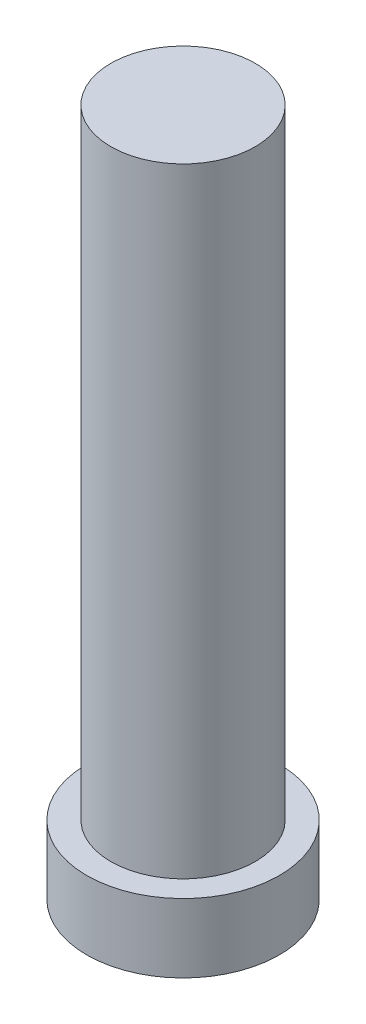
SolidWorks part; units mm, degrees
ref_plane "Front Plane" through (0, 0, 0) normal (0, 0, 1) x (1, 0, 0)
ref_plane "Top Plane" through (0, 0, 0) normal (0, 1, 0) x (1, 0, 0)
ref_plane "Right Plane" through (0, 0, 0) normal (1, 0, 0) x (0, 0, -1)
sketch "Sketch1" plane through (0, 0, 0) normal (0, 1, 0) x (1, 0, 0)
  circle A0 centre (0, 0) radius 1.778
  dimension "D1" = 3.556
extrude "Boss-Extrude1" add sketch "Sketch1" along normal blind 1.27
sketch "Sketch3" plane through (0, 1.27, 0) normal (0, 1, 0) x (1, 0, 0)
  circle A0 centre (0, 0) radius 1.3335
  dimension "D1" = 2.667
extrude "Boss-Extrude2" add sketch "Sketch3" along normal blind 11.43
